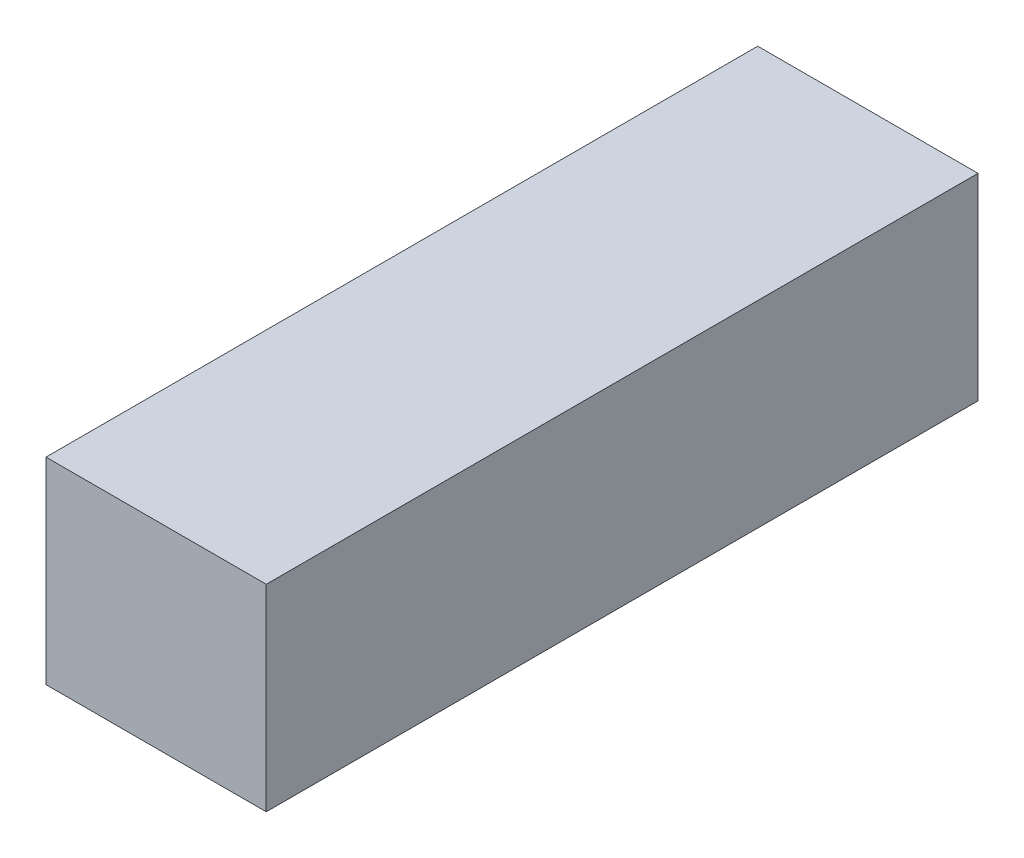
SolidWorks part; units mm, degrees
ref_plane "Front Plane" through (0, 0, 0) normal (0, 0, 1) x (1, 0, 0)
ref_plane "Top Plane" through (0, 0, 0) normal (0, 1, 0) x (1, 0, 0)
ref_plane "Right Plane" through (0, 0, 0) normal (1, 0, 0) x (0, 0, -1)
sketch "Sketch1" plane through (0, 0, 0) normal (0, 1, 0) x (1, 0, 0)
  line L1 (0, 0) -> (48.26, 0)
  line L2 (0, 0) -> (0, 155.956)
  line L3 (0, 155.956) -> (48.26, 155.956)
  line L4 (48.26, 0) -> (48.26, 155.956)
  dimension "D1" = 155.956
  dimension "D2" = 48.26
extrude "Boss-Extrude1" add sketch "Sketch1" along normal blind 43.18
